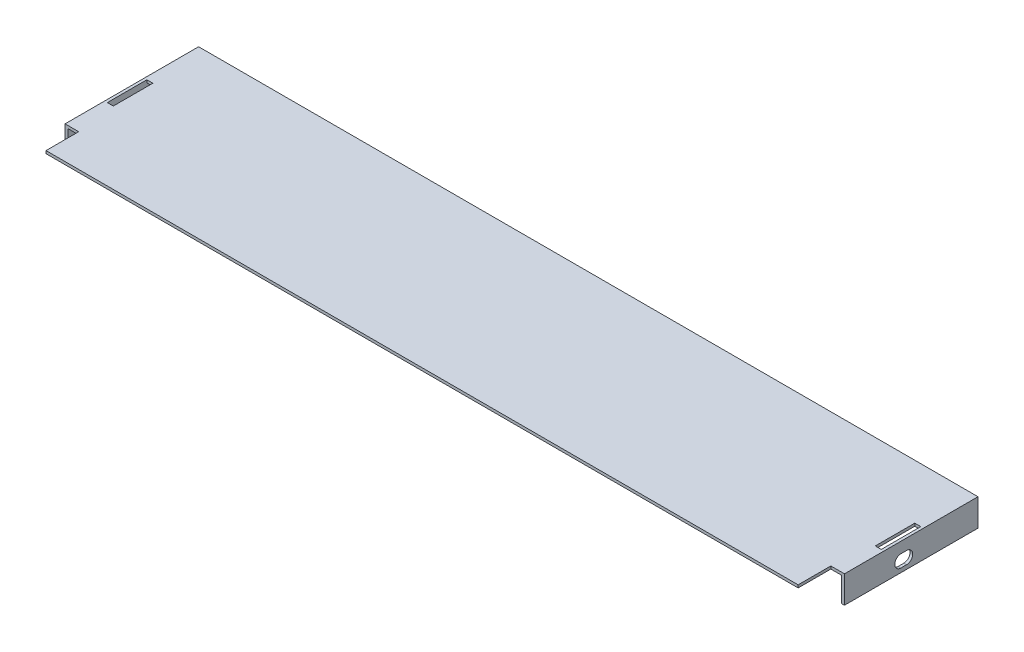
SolidWorks part; units mm, degrees
ref_plane "Спереди" through (0, 0, 0) normal (0, 0, 1) x (1, 0, 0)
ref_plane "Сверху" through (0, 0, 0) normal (0, 1, 0) x (1, 0, 0)
ref_plane "Справа" through (0, 0, 0) normal (1, 0, 0) x (0, 0, -1)
sketch "Эскиз1" plane through (0, 0, 0) normal (0, 1, 0) x (1, 0, 0)
  line L0 (138, -30.5) -> (138, -18.5)
  line L1 (-138, -30.5) -> (138, -30.5)
  line L2 (-143, -18.5) -> (-143, 30.5)
  line L3 (-143, 30.5) -> (143, 30.5)
  line L4 (143, -18.5) -> (143, 30.5)
  line L5 (-141.0873, -30.0921) -> (143, 30.5) construction
  line L6 (-143, 30.5) -> (143, -30.5) construction
  line L7 (139.8, 10.5) -> (142, 10.5)
  line L8 (139.8, 10.5) -> (139.8, -4)
  line L9 (139.8, -4) -> (142, -4)
  line L10 (142, 10.5) -> (142, -4)
  line L11 (139.8, 10.5) -> (142, -4) construction
  line L12 (139.8, -4) -> (142, 10.5) construction
  line L13 (138, -18.5) -> (143, -18.5)
  line L14 (0, 67.4958) -> (0, -67.4958) construction
  line L15 (-138, -18.5) -> (-143, -18.5)
  line L16 (-138, -30.5) -> (-138, -18.5)
  line L17 (-139.8, -4) -> (-142, -4)
  line L18 (-142, 10.5) -> (-142, -4)
  line L19 (-139.8, 10.5) -> (-142, 10.5)
  line L20 (-139.8, 10.5) -> (-139.8, -4)
  point P0 (0, 0)
  point P6 (140.9, 3.25)
  point P16 (0, 0)
  dimension "D1" = 286
  dimension "D2" = 61
  dimension "D3" = 2.2
  dimension "D4" = 1
  dimension "D5" = 20
  dimension "D6" = 14.5
  dimension "D7" = 12
  dimension "D8" = 5
extrude "Бобышка-Вытянуть1" add sketch "Эскиз1" along normal blind 1
sketch "Эскиз2" plane through (0, 0, 0) normal (0, -1, 0) x (1, 0, 0)
  line L0 (-143, 18.5) -> (-143, -30.5)
  line L1 (-143, -30.5) -> (143, -30.5)
  line L2 (143, -30.5) -> (143, 18.5)
  line L3 (143, 18.5) -> (142, 18.5)
  line L4 (138, 18.5) -> (143, 18.5) construction
  line L5 (142, 18.5) -> (142, -29.5)
  line L6 (142, -29.5) -> (-142, -29.5)
  line L7 (-142, -29.5) -> (-142, 18.5)
  line L8 (-143, 18.5) -> (-138, 18.5) construction
  line L9 (-142, 18.5) -> (-143, 18.5)
  dimension "D1" = 1
  dimension "D2" = 1
  dimension "D3" = 1
extrude "Бобышка-Вытянуть2" add sketch "Эскиз2" along normal blind 9
sketch "Эскиз3" plane through (143, 0, 0) normal (1, 0, 0) x (0, 0, -1)
  line L0 (2.2, -3) -> (4.3, -3)
  line L1 (2.2, -7.5) -> (4.3, -7.5)
  line L2 (-18.5, 1) -> (30.5, 1) construction
  line L3 (10.5, 1) -> (-4, 1) construction
  arc A0 (4.3, -3) -> (4.3, -7.5) centre (4.3, -5.25) cw
  arc A1 (2.2, -7.5) -> (2.2, -3) centre (2.2, -5.25) cw
  point P4 (3.25, -3)
  point P7 (6.55, -5.25)
  point P8 (-0.05, -5.25)
  point P9 (0.4752, -4.2829)
  point P12 (3.25, 1)
  point P13 (0, 0)
  point P14 (0.2, -3.3702)
  dimension "D1" = 4.5
  dimension "D2" = 6.6
  dimension "D3" = 4
extrude "Вырез-Вытянуть1" cut sketch "Эскиз3" against normal through all contours L0 A0 L1 A1
